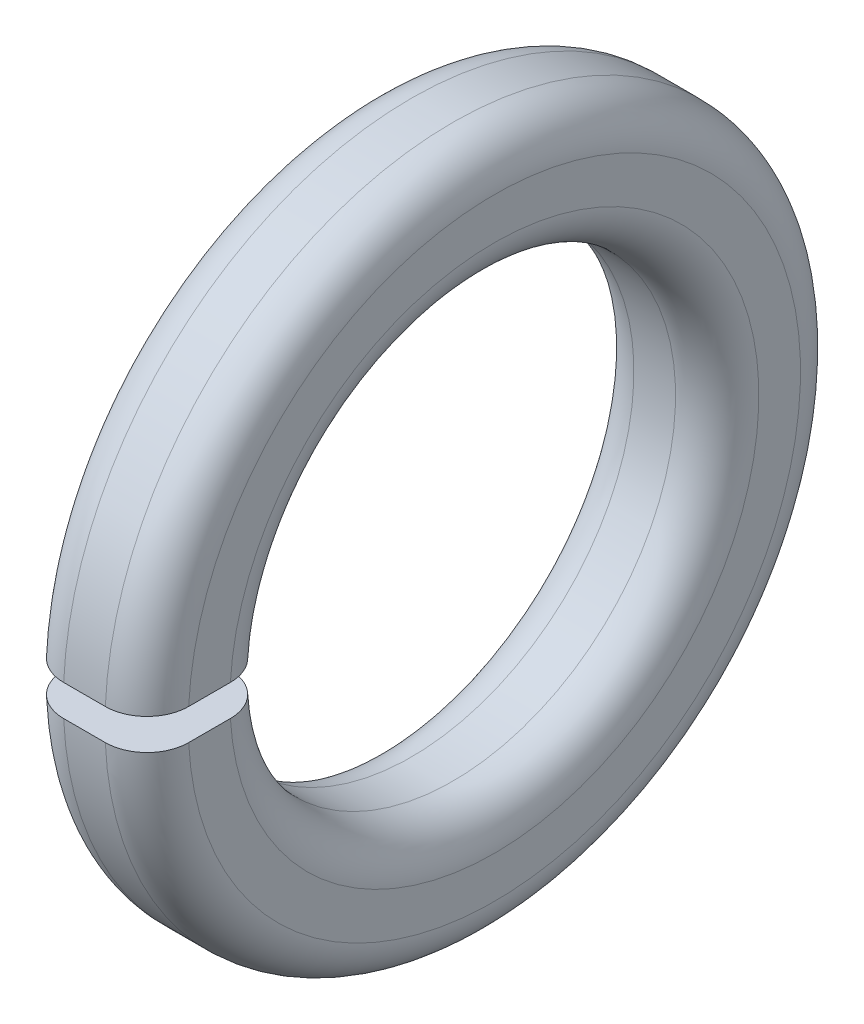
SolidWorks part; units mm, degrees
ref_plane "Plane1" through (0, 0, 0) normal (0, 0, 1) x (1, 0, 0)
ref_plane "Plane2" through (0, 0, 0) normal (0, 1, 0) x (1, 0, 0)
ref_plane "Plane3" through (0, 0, 0) normal (1, 0, 0) x (0, 0, -1)
sketch "Sketch1" plane through (0, 0, 0) normal (0, 0, 1) x (1, 0, 0)
  line L0 (-34.925, 0) -> (9.525, 0) construction
  line L1 (0, 3.175) -> (0, 3.675)
  line L2 (-0.5, 4.175) -> (-1, 4.175)
  line L3 (-1.5, 3.675) -> (-1.5, 3.175)
  line L4 (-1, 2.675) -> (-0.5, 2.675)
  arc A0 (-1, 2.675) -> (-1.5, 3.175) centre (-1, 3.175) cw
  arc A1 (0, 3.175) -> (-0.5, 2.675) centre (-0.5, 3.175) cw
  arc A2 (0, 3.675) -> (-0.5, 4.175) centre (-0.5, 3.675) ccw
  arc A3 (-1, 4.175) -> (-1.5, 3.675) centre (-1, 3.675) ccw
  point P8 (-1.5, 2.675)
  point P14 (0, 4.175)
  point P17 (-1.5, 4.175)
  dimension "Fillet_rad" = 0.5
  dimension "Thickness" = 1.5
  dimension "Inside_dia" = 5.35
  dimension "Outside_dia" = 8.35
revolve "Base-Revolve" add sketch "Sketch1" angle 360 about L0
sketch "Sketch2" plane through (0, 0, 0) normal (-1, 0, 0) x (0, -1, 0)
  line L0 (-0.1875, 0) -> (0.1875, 0)
  line L1 (0, 0) -> (0, 12.7) construction
  line L2 (0.1875, 0) -> (0.1875, 4.2585)
  line L3 (0.1875, 4.2585) -> (-0.1875, 4.2585)
  line L4 (-0.1875, 4.2585) -> (-0.1875, 0)
  dimension "D1" = 0.375
  dimension "D2" = 4.2585
extrude "Gap" cut sketch "Sketch2" along normal through all
equation "\"D1@Sketch2\" = \"Thickness@Sketch1\" * 0.25"
equation "\"Outside_dia@Sketch1\" = \"Inside_dia@Sketch1\" + 2.0 * \"Thickness@Sketch1\""
equation "\"D2@Sketch2\" = \"Outside_dia@Sketch1\" * 0.51"
